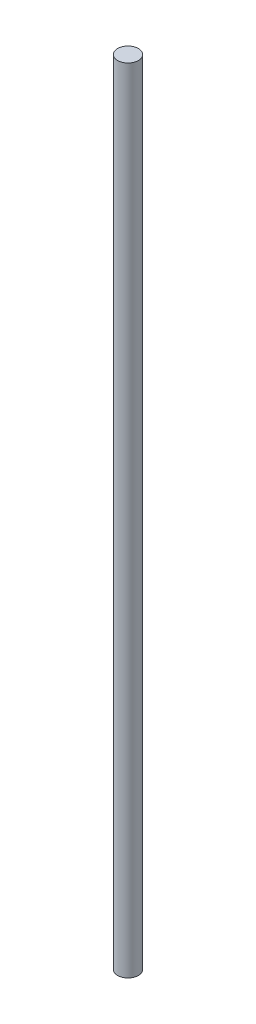
SolidWorks part; units mm, degrees
ref_plane "Front Plane" through (0, 0, 0) normal (0, 0, 1) x (1, 0, 0)
ref_plane "Top Plane" through (0, 0, 0) normal (0, 1, 0) x (1, 0, 0)
ref_plane "Right Plane" through (0, 0, 0) normal (1, 0, 0) x (0, 0, -1)
sketch "Sketch1" plane through (0, 0, 0) normal (0, 1, 0) x (1, 0, 0)
  circle A0 centre (0, 0) radius 2.5
  dimension "D1" = 5
extrude "Boss-Extrude1" add sketch "Sketch1" along normal offset from surface (190 mm away) 10
